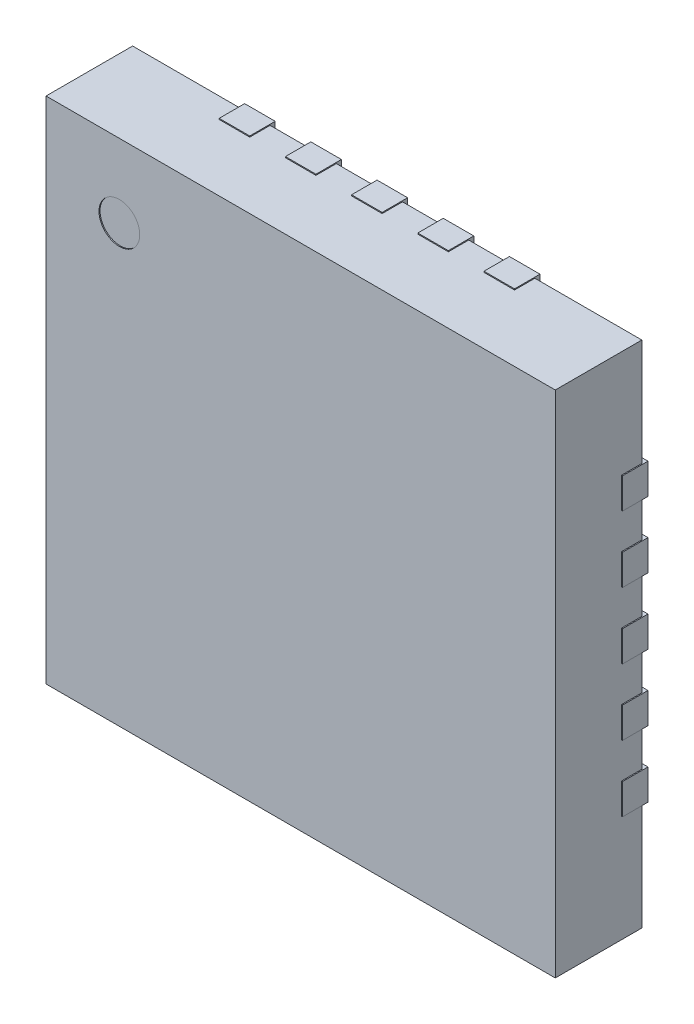
SolidWorks part; units mm, degrees
ref_plane "Front Plane" through (0, 0, 0) normal (0, 0, 1) x (1, 0, 0)
ref_plane "Top Plane" through (0, 0, 0) normal (0, 1, 0) x (1, 0, 0)
ref_plane "Right Plane" through (0, 0, 0) normal (1, 0, 0) x (0, 0, -1)
sketch "Sketch1" plane through (0, 0, 0) normal (0, 0, 1) x (1, 0, 0)
  line L1 (-2.5, 2.5) -> (2.5, 2.5)
  line L2 (-2.5, 2.5) -> (-2.5, -2.5)
  line L3 (-2.5, -2.5) -> (2.5, -2.5)
  line L4 (2.5, 2.5) -> (2.5, -2.5)
  line L5 (-2.5, 2.5) -> (2.5, -2.5) construction
  line L6 (-2.5, -2.5) -> (2.5, 2.5) construction
  point P0 (0, 0)
  dimension "D1" = 5
  dimension "D2" = 5
extrude "Boss-Extrude1" add sketch "Sketch1" along normal blind 0.85 contours L4 L3 L2 L1
sketch "Sketch2" plane through (0, 0, 0.85) normal (0, 0, 1) x (1, 0, 0)
  line L0 (-1.78, 1.78) -> (-1.78, 2.5) construction
  line L1 (-2.5, 2.5) -> (2.5, 2.5) construction
  line L2 (-1.78, 1.78) -> (-2.5, 1.78) construction
  line L3 (-2.5, 2.5) -> (-2.5, -2.5) construction
  circle A0 centre (-1.78, 1.78) radius 0.2
  dimension "D1" = 0.4
  dimension "D2" = 0.72
extrude "Cut-Extrude1" cut sketch "Sketch2" against normal blind 0.01
sketch "Sketch3" plane through (0, 0, 0) normal (0, 0, -1) x (-1, 0, 0)
  line L1 (1.4625, -1.625) -> (-1.4625, -1.625)
  line L2 (1.625, -1.4625) -> (1.625, 1.4625)
  line L3 (1.4625, 1.625) -> (-1.4625, 1.625)
  line L4 (-1.625, -1.4625) -> (-1.625, 1.4625)
  line L5 (1.625, -1.625) -> (-1.625, 1.625) construction
  line L6 (1.625, 1.625) -> (-1.625, -1.625) construction
  arc A0 (-1.4625, -1.625) -> (-1.625, -1.4625) centre (-1.4625, -1.4625) cw
  arc A1 (-1.4625, 1.625) -> (-1.625, 1.4625) centre (-1.4625, 1.4625) ccw
  arc A2 (1.625, 1.4625) -> (1.4625, 1.625) centre (1.4625, 1.4625) ccw
  arc A3 (1.625, -1.4625) -> (1.4625, -1.625) centre (1.4625, -1.4625) cw
  point P0 (0, 0)
  dimension "D3" = 0.1625
  dimension "D1" = 3.25
  dimension "D2" = 3.25
extrude "Boss-Extrude2" add sketch "Sketch3" along normal blind 0.05
sketch "Sketch5" plane through (0, 0, 0) normal (0, 0, -1) x (-1, 0, 0)
  line L0 (2.25, 1.45) -> (2.5, 1.45)
  line L2 (2.25, 1.15) -> (2.5, 1.15)
  line L6 (2.5, 1.45) -> (2.51, 1.45)
  line L7 (2.51, 1.45) -> (2.51, 1.15)
  line L8 (2.51, 1.15) -> (2.5, 1.15)
  line L9 (2.5, 2.5) -> (2.5, -2.5) construction
  arc A0 (2.25, 1.45) -> (2.25, 1.15) centre (2.25, 1.3) ccw
  point P8 (2.1, 1.3)
  dimension "D2" = 0.01
  dimension "D3" = 0.4
  dimension "D4" = 1.3
  dimension "D1" = 0.3
extrude "Boss-Extrude3" add sketch "Sketch5" along normal blind 0.05 and the other way blind 0.2
pattern_linear "LPattern1" count 5 spacing 0.65 along (0, -1, 0) of "Boss-Extrude3"
mirror "Mirror1" about plane through (0, 0, 0) normal (1, 0, 0) of "LPattern1", "Boss-Extrude3"
sketch "Sketch6" plane through (0, 0, 0) normal (0, 0, -1) x (-1, 0, 0)
  line L0 (-1.45, 2.51) -> (-1.15, 2.51)
  line L1 (-1.15, 2.51) -> (-1.15, 2.5)
  line L2 (2.5, 2.5) -> (-2.5, 2.5) construction
  line L3 (-1.15, 2.5) -> (-1.15, 2.25)
  line L4 (-1.45, 2.51) -> (-1.45, 2.5)
  line L5 (-1.45, 2.5) -> (-1.45, 2.25)
  arc A0 (-1.45, 2.25) -> (-1.15, 2.25) centre (-1.3, 2.25) ccw
  point P9 (-1.3, 2.1)
  dimension "D3" = 0.4
  dimension "D4" = 1.3
  dimension "D1" = 0.01
  dimension "D2" = 0.3
extrude "Boss-Extrude4" add sketch "Sketch6" along normal blind 0.05 and the other way blind 0.2
pattern_linear "LPattern2" count 5 spacing 0.65 along (-1, 0, 0) of "Boss-Extrude4"
mirror "Mirror2" about plane through (0, 0, 0) normal (0, 1, 0) of "LPattern2", "Boss-Extrude4"
sketch "Sketch4" plane through (0, 0, -0.05) normal (0, 0, -1) x (-1, 0, 0)
  line L0 (1.625, -1.4625) -> (1.625, 1.4625) construction
  line L1 (1.625, -1.4625) -> (1.625, 1.4625) construction
  line L2 (1.625, 0.7719) -> (1.625, 0.5281)
  arc A0 (1.625, 0.7719) -> (1.625, 0.5281) centre (1.625, 0.65) ccw
  arc A1 (2.25, 0.8) -> (2.25, 0.5) centre (2.25, 0.65) ccw construction
  point P11 (2.1, 0.65)
  dimension "D1" = 0.1219
extrude "Cut-Extrude2" [suppressed] cut sketch "Sketch4" against normal up to surface (0.05 mm away)
equation "\"E\" = 5"
equation "\"D\" = 5"
equation "\"H\"= \"A\" + \"A1\""
equation "\"D1@Boss-Extrude1\"=\"H\""
equation "\"D2@Sketch1\"=\"E\""
equation "\"D1@Sketch1\"=\"D\""
equation "\"D2\" = 3.25"
equation "\"E2\" = 3.25"
equation "\"L\"= 0.4"
equation "\"b\" = 0.3"
equation "\"e_\" = 0.65"
equation "\"A3\"= 0.2"
equation "\"K\"= 0.2"
equation "\"A1\"= 0.05"
equation "\"D1@Sketch3\"=\"D2\""
equation "\"D2@Sketch3\"=\"E2\""
equation "\"GND_R\"= ( \"D2\" + \"E2\" ) / 2 * 0.05"
equation "\"D3@Sketch3\"=\"GND_R\""
equation "\"D1@Boss-Extrude2\"=\"A1\""
equation "\"D1@Sketch4\"=\"GND_R\"*0.75"
equation "\"Px\" = 5"
equation "\"Py\" = 5"
equation "\"P\"= 2 * \"Px\" + 2 * \"Py\""
equation "\"D1@Boss-Extrude3\"=\"A1\""
equation "\"D2@Boss-Extrude3\"=\"A3\""
equation "\"D3@Sketch5\"=\"L\""
equation "\"D4@Sketch5\"=(\"Py\"/2-1)*\"e_\"+\"e_\"/2"
equation "\"D3@LPattern1\"=\"e_\""
equation "\"D1@LPattern1\"=\"Py\""
equation "\"D1@Sketch5\"=\"b\""
equation "\"D1@Sketch6\"=\"D2@Sketch5\""
equation "\"D2@Sketch6\"=\"b\""
equation "\"D3@Sketch6\"=\"L\""
equation "\"D4@Sketch6\"=(\"Px\"/2-1)*\"e_\"+\"e_\"/2"
equation "\"D1@Boss-Extrude4\"=\"A1\""
equation "\"D2@Boss-Extrude4\"=\"A3\""
equation "\"D3@LPattern2\"=\"e_\""
equation "\"D1@LPattern2\"=\"Px\""
equation "\"A\" = 0.8"
equation "\"D2@Sketch2\"=\"D1@Sketch2\"*1.8"
